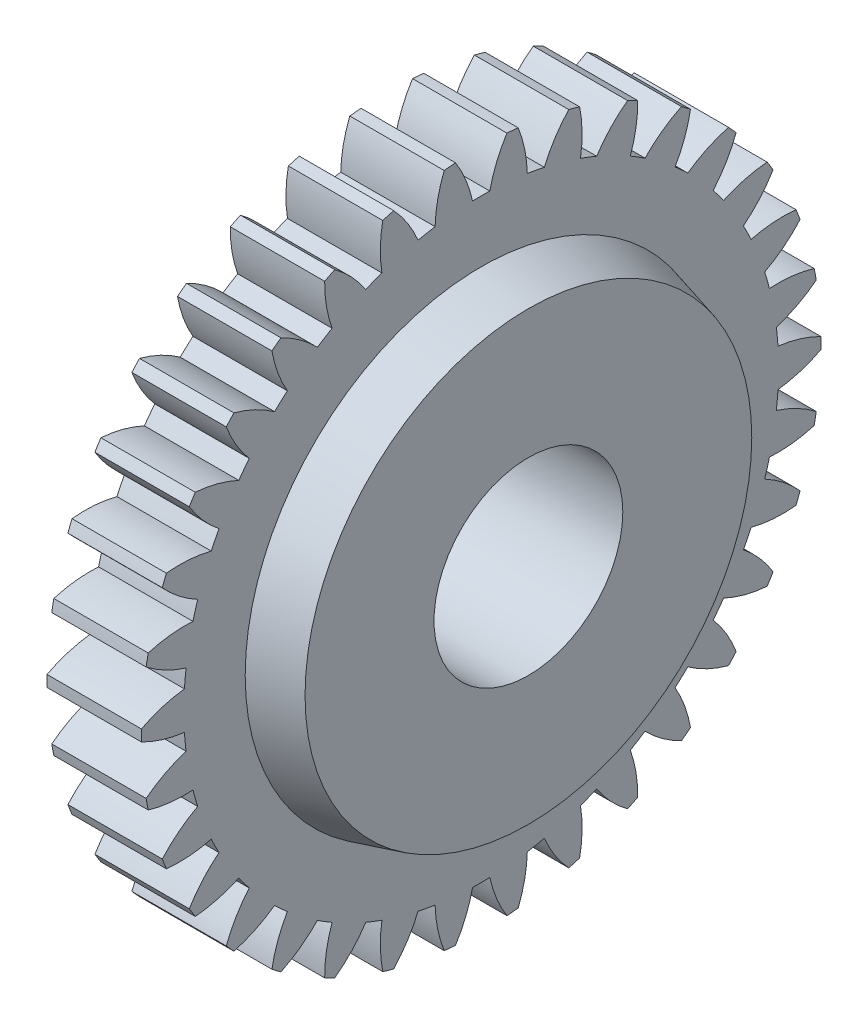
SolidWorks part; units mm, degrees
ref_plane "Plane1" through (0, 0, 0) normal (0, 0, 1) x (1, 0, 0)
ref_plane "Plane2" through (0, 0, 0) normal (0, 1, 0) x (1, 0, 0)
ref_plane "Plane3" through (0, 0, 0) normal (1, 0, 0) x (0, 0, -1)
sketch "HoldingSke" plane through (0, 0, 0) normal (0, 1, 0) x (1, 0, 0)
  line L0 (0, 0) -> (1.3817, -0.932)
  line L1 (-15, 0) -> (100, 0) construction
  line L2 (0, 0) -> (-2.1039, 2.3779)
  line L3 (0, 0) -> (-11.863, 4.5341)
  line L4 (0, 0) -> (7.1596, 4.8292)
  line L5 (0, 0) -> (-46.8476, -17.4728)
  line L6 (0, 0) -> (-2.4869, -1.6779)
  line L7 (-2.1039, 2.3779) -> (8.6587, 51.2062)
  line L8 (-76.2, 54.61) -> (-75.2, 54.61)
  line L9 (-71.009, 38.7566) -> (-53.1078, 45.2721)
  line L10 (-76.2, 71.12) -> (104.1128, 71.12)
  line L11 (0, 0) -> (-3, 0)
  line L12 (-76.2, 101.6) -> (-76.177, 101.6)
  line L13 (24.9733, 27.94) -> (52.9518, 28.4284)
  line L14 (24.9733, 27.94) -> (24.9743, 27.94)
  line L15 (24.9733, 27.94) -> (100.4006, 29.5858)
  line L16 (-63.627, -0.6) -> (-12.827, -0.6)
  circle A0 centre (0, 0) radius 3
  circle A1 centre (0, 0) radius 3.149
  circle A2 centre (0, 0) radius 37.5
  circle A3 centre (0, 0) radius 3
  dimension "MHD" = 6.298
  dimension "Hub_dia" = 75
  dimension "Bore" = 6
  dimension "MBD" = 6
  dimension "Num_teeth" = 34
  dimension "Pitch" = 1.6667
  dimension "Overall_len" = 50
  dimension "Show_teeth" = 34
  dimension "Thickness" = 3
  dimension "OAL" = 50.0004
  dimension "T_dim" = 1
  dimension "Ap" = 20
  dimension "H" = 19.05
  dimension "Pitch_radius" = 180.3128
  dimension "Width" = 3
  dimension "Backlash" = 0.023
  dimension "Addendum_fac" = 1
  dimension "Dedendum_fac" = 1.25
  dimension "Clearance_fac" = 0.25
  dimension "Dedendum_add" = 0.001
  dimension "Module" = 0.6
sketch "BasProSke" plane through (0, 0, 0) normal (0, 1, 0) x (1, 0, 0)
  line L0 (-10, 0) -> (60, 0) construction
  line L1 (0, 0) -> (0, 10.8)
  line L2 (0, 0) -> (3, 0)
  line L3 (3, 0) -> (3, 10.8)
  line L4 (3, 10.8) -> (0, 10.8)
  dimension "Thickness" = 3
  dimension "Diameter" = 21.6
revolve "Base-Revolve" add sketch "BasProSke" angle 360 about L0
sketch "TooCutSke" plane through (0, 0, 0) normal (1, 0, 0) x (0, 0, -1)
  line L1 (0, 0) -> (0, 107) construction
  line L2 (0, 0) -> (-0.5113, 10.1872) construction
  line L3 (0, 0) -> (-1.8806, 20.2948) construction
  line L4 (-0.5113, 10.1872) -> (-0.9403, 10.1474) construction
  arc A0 (0.2751, 9.445) -> (-0.2751, 9.445) centre (0, 0) ccw
  arc A1 (0.833, 10.7933) -> (-0.833, 10.7933) centre (0, 0) ccw
  circle A2 centre (0, 0) radius 10.2 construction
  circle A3 centre (0, 0) radius 9.5849 construction
  arc A4 (-0.2751, 9.445) -> (-0.833, 10.7933) centre (-4.2634, 8.5845) ccw
  arc A5 (0.833, 10.7933) -> (0.2751, 9.445) centre (4.2634, 8.5845) ccw
  dimension "Root_dia" = 18.898
  dimension "Overcut_dia" = 21.6508
  dimension "Pitch_dia" = 20.4
  dimension "Base_dia" = 19.1697
  dimension "Flank_rad" = 4.08
  dimension "Half_ang" = 5.294
  dimension "Half_CT" = 0.4308
extrude "ToothCut" cut sketch "TooCutSke" along normal through all
fillet "Breaks" [suppressed] radius 0.012
fillet "RootFillets" [suppressed] radius 0.151
pattern_circular "TeethCuts" count 34 every 10.588 about axis through (-10, 0, 0) along (1, 0, 0) of "ToothCut", "RootFillets", "Breaks"
sketch "HubNeaOneSke" plane through (0, 0, 0) normal (-1, 0, 0) x (0, 0, 1)
  circle A0 centre (0, 0) radius 3.149
  dimension "Diameter" = 6.298
extrude "HubNearOne" [suppressed] add sketch "HubNeaOneSke" along normal blind 47.0004
sketch "HubNeaBotSke" plane through (0, 0, 0) normal (-1, 0, 0) x (0, 0, 1)
  circle A0 centre (0, 0) radius 3.149
  dimension "Diameter" = 6.298
extrude "HubNearBoth" [suppressed] add sketch "HubNeaBotSke" along normal blind 23.5002
ref_plane "FarPln" through (3, 0, 0) normal (1, 0, 0) x (0, 0, -1)
sketch "Sketch1" plane through (3, 0, 0) normal (1, 0, 0) x (0, 0, -1)
  circle A0 centre (0, 0) radius 7.5
  dimension "D1" = 15
extrude "Boss-Extrude1" add sketch "Sketch1" along normal blind 1.5 draft 15
sketch "HubFarSke" plane through (3, 0, 0) normal (1, 0, 0) x (0, 0, -1)
  circle A0 centre (0, 0) radius 3.149
  dimension "Diameter" = 6.298
extrude "HubFar" [suppressed] add sketch "HubFarSke" along normal blind 23.5002
sketch "BorSke" plane through (0, 0, 0) normal (1, 0, 0) x (0, 0, -1)
  circle A0 centre (0, 0) radius 3
  dimension "Diameter" = 6
extrude "Bore" cut sketch "BorSke" along normal mid plane 100.0008
sketch "KeySke" plane through (0, 0, 0) normal (1, 0, 0) x (0, 0, -1)
  line L0 (-1, 0) -> (-1, 4)
  line L1 (-1, 4) -> (1, 4)
  line L2 (1, 4) -> (1, 0)
  line L3 (0, 0) -> (0, 34) construction
  line L4 (-1, 0) -> (1, 0)
  dimension "Offset" = 4
  dimension "Width" = 2
extrude "Keyway" [suppressed] cut sketch "KeySke" along normal mid plane 100.0008
pattern_circular "Keyway2" [suppressed] count 2 every 90 about axis through (-10, 0, 0) along (1, 0, 0)
equation "' \"Module@HoldingSke\" = 6.35"
equation "\"Num_teeth@HoldingSke\"= 34 '\"Num_teeth@HoldingSke\" = 13\"Num_teeth@HoldingSke\" = 34"
equation "'\"Num_teeth@HoldingSke\" = 13\"Num_teeth@HoldingSke\" = 34"
equation "'\"Ap@HoldingSke\" =  20"
equation "'\"Ap@HoldingSke\" = 20"
equation "' \"Width@HoldingSke\" = 0.5 * 25.4"
equation "' \"Hub_dia@HoldingSke\"= 1 * 25.4"
equation "' \"Hub_dia@HoldingSke\" = 1 * 25.4"
equation "' \"Overall_len@HoldingSke\" = 1.0 * 25.4"
equation "' \"Bore@HoldingSke\" = 0.75 * 25.4"
equation "' \"T_dim@HoldingSke\" = 0.1 * 25.4"
equation "' \"Width@KeySke\" = 0.25 * 25.4"
equation "\"Show_teeth@HoldingSke\"= 34 '\"Show_teeth@HoldingSke\" = 13'\"Show_teeth@HoldingSke\" = 34"
equation "'\"Show_teeth@HoldingSke\" = 13'\"Show_teeth@HoldingSke\" = 34"
equation "' \"Backlash@HoldingSke\" = 0.009 * 25.4"
equation "' \"Addendum_fac@HoldingSke\" = 1.0"
equation "' \"Dedendum_fac@HoldingSke\" = 1.25"
equation "' \"Dedendum_add@HoldingSke\" = 0.00005 * 25.4"
equation "' \"Clearance_fac@HoldingSke\" = 0.25"
equation "\"Pitch@HoldingSke\" = 1 / \"Module@HoldingSke\""
equation "\"Overcut_dia@TooCutSke\" = (\"Num_teeth@HoldingSke\" + 2 * \"Addendum_fac@HoldingSke\") / \"Pitch@HoldingSke\" + 0.002 * 25.4"
equation "\"Pitch_dia@TooCutSke\" = \"Num_teeth@HoldingSke\" / \"Pitch@HoldingSke\""
equation "\"Base_dia@TooCutSke\" = \"Num_teeth@HoldingSke\" / \"Pitch@HoldingSke\" * cos((\"Ap@HoldingSke\"  * 3.14159265 / 180))"
equation "\"Root_dia@TooCutSke\" = (\"Num_teeth@HoldingSke\" + 2) / \"Pitch@HoldingSke\" - 2 * (\"Addendum_fac@HoldingSke\" + \"Dedendum_fac@HoldingSke\") / \"Pitch@HoldingSke\" - \"Dedendum_add@HoldingSke\" * 2"
equation "\"Half_ang@TooCutSke\" = 180 / \"Num_teeth@HoldingSke\""
equation "\"Half_CT@TooCutSke\" = \"Num_teeth@HoldingSke\" / \"Pitch@HoldingSke\" * sin((3.14159265 / 2 / \"Num_teeth@HoldingSke\")) / 2 - 7 * \"Backlash@HoldingSke\" / 4"
equation "\"Flank_rad@TooCutSke\" = \"Num_teeth@HoldingSke\" / \"Pitch@HoldingSke\" / 5"
equation "\"Radius@RootFillets\" = \"Clearance_fac@HoldingSke\" / \"Pitch@HoldingSke\" + \"Dedendum_add@HoldingSke\""
equation "\"Break_rad@Breaks\" = 0.02 / \"Pitch@HoldingSke\""
equation "\"Thickness@HoldingSke\" = \"Width@HoldingSke\""
equation "\"OAL@HoldingSke\" = \"Thickness@HoldingSke\""
equation "\"MHD@HoldingSke\" = (\"Num_teeth@HoldingSke\" + 2) / \"Pitch@HoldingSke\" - 2 * (\"Addendum_fac@HoldingSke\" + \"Dedendum_fac@HoldingSke\")  / \"Pitch@HoldingSke\" - \"Dedendum_add@HoldingSke\" * 2"
equation "\"MBD@HoldingSke\" = (\"Num_teeth@HoldingSke\" + 2) / \"Pitch@HoldingSke\" - 2 * (\"Addendum_fac@HoldingSke\" + \"Dedendum_fac@HoldingSke\")  / \"Pitch@HoldingSke\" - \"Dedendum_add@HoldingSke\" * 2 - 0.002 * 25.4"
equation "\"MHD@HoldingSke\" = ((sgn( \"MHD@HoldingSke\" - \"Hub_dia@HoldingSke\" )-1)*( \"MHD@HoldingSke\" - \"Hub_dia@HoldingSke\" ))/-2+ \"Hub_dia@HoldingSke\""
equation "\"MBD@HoldingSke\" = ((sgn( \"MBD@HoldingSke\" - \"Bore@HoldingSke\" )-1)*( \"MBD@HoldingSke\" - \"Bore@HoldingSke\" ))/-2+ \"Bore@HoldingSke\""
equation "\"OAL@HoldingSke\" = ((sgn( \"OAL@HoldingSke\" - \"Overall_len@HoldingSke\" )+1)*( \"OAL@HoldingSke\" - \"Overall_len@HoldingSke\" ))/2 + \"Overall_len@HoldingSke\" + 0.000002 * 25.4"
equation "\"Num_teeth@TeethCuts\" = int( \"Show_teeth@HoldingSke\" ) + 1"
equation "\"Num_teeth@TeethCuts\" = ((sgn( \"Num_teeth@TeethCuts\" - \"Num_teeth@HoldingSke\" )-1)*( \"Num_teeth@TeethCuts\" - \"Num_teeth@HoldingSke\" ))/-2+ \"Num_teeth@HoldingSke\""
equation "\"Num_teeth@TeethCuts\"= 34"
equation "\"Angle@TeethCuts\" = 360.0 / \"Num_teeth@HoldingSke\""
equation "\"Diameter@BasProSke\" = (\"Num_teeth@HoldingSke\" + 2 * \"Addendum_fac@HoldingSke\") / \"Pitch@HoldingSke\""
equation "\"Thickness@BasProSke\"  = \"Thickness@HoldingSke\""
equation "' \"Fillet_rad@BasProSke\" =  \"Thickness@HoldingSke\" * 0.05"
equation "' \"Fillet_rad@BasProSke\" = \"Thickness@HoldingSke\" * 0.05"
equation "\"MHD@HoldingSke\" = ((sgn( \"MHD@HoldingSke\" - \"Root_dia@TooCutSke\" )-1)*( \"MHD@HoldingSke\" - \"Root_dia@TooCutSke\" ))/-2+ \"Root_dia@TooCutSke\""
equation "\"Diameter@HubNeaOneSke\" = \"MHD@HoldingSke\""
equation "\"Length@HubNearOne\" = \"OAL@HoldingSke\" - \"Thickness@BasProSke\""
equation "\"Diameter@HubNeaBotSke\" = \"MHD@HoldingSke\""
equation "\"Length@HubNearBoth\" = ( \"OAL@HoldingSke\" - \"Thickness@BasProSke\" ) / 2.0"
equation "\"Thickness@FarPln\" = \"Thickness@BasProSke\""
equation "\"Diameter@HubFarSke\" = \"MHD@HoldingSke\""
equation "\"Length@HubFar\" = ( \"OAL@HoldingSke\" - \"Thickness@BasProSke\" ) / 2.0"
equation "\"Diameter@BorSke\" = \"MBD@HoldingSke\""
equation "\"D1@Bore\" = \"OAL@HoldingSke\" * 2.0"
equation "\"D1@Keyway\" = \"OAL@HoldingSke\" * 2.0"
equation "\"Offset@KeySke\" = \"T_dim@HoldingSke\" + \"MBD@HoldingSke\" / 2.0"
